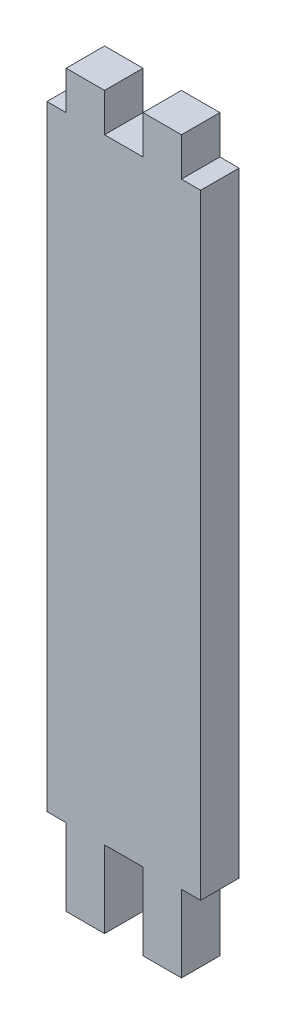
SolidWorks part; units mm, degrees
ref_plane "Front Plane" through (0, 0, 0) normal (0, 0, 1) x (1, 0, 0)
ref_plane "Top Plane" through (0, 0, 0) normal (0, 1, 0) x (1, 0, 0)
ref_plane "Right Plane" through (0, 0, 0) normal (1, 0, 0) x (0, 0, -1)
sketch "Sketch1" plane through (0, 0, 0) normal (0, 0, 1) x (1, 0, 0)
  line L0 (-7.5, 40) -> (-7.5, 45)
  line L1 (-10, -40) -> (-7.5, -40)
  line L2 (-10, -40) -> (-10, 40)
  line L3 (-10, 40) -> (-7.5, 40)
  line L4 (10, -40) -> (10, 40)
  line L5 (-10, -40) -> (10, 40) construction
  line L6 (-10, 40) -> (10, -40) construction
  line L7 (-7.5, 45) -> (-2.5, 45)
  line L8 (-2.5, 45) -> (-2.5, 40)
  line L9 (2.5, 40) -> (2.5, 45)
  line L10 (2.5, 45) -> (7.5, 45)
  line L11 (7.5, 45) -> (7.5, 40)
  line L12 (-2.5, 40) -> (2.5, 40)
  line L13 (7.5, 40) -> (10, 40)
  line L14 (-2.5, -40) -> (2.5, -40)
  line L16 (-7.5, -40) -> (-7.5, -45)
  line L20 (2.5, -40) -> (2.5, -45)
  line L23 (7.5, -40) -> (10, -40)
  line L24 (-7.5, -45) -> (-7.5, -50)
  line L25 (-7.5, -50) -> (-2.5, -50)
  line L26 (-2.5, -50) -> (-2.5, -40)
  line L27 (2.5, -45) -> (2.5, -50)
  line L28 (2.5, -50) -> (7.5, -50)
  line L29 (7.5, -50) -> (7.5, -40)
  point P0 (0, 0)
  point P19 (0, 0)
  point P24 (7.5, -45.7393)
  point P27 (-2.5, -45.954)
  dimension "D1" = 5
  dimension "D2" = 5
  dimension "D3" = 20
  dimension "D4" = 5
  dimension "D5" = 80
  dimension "D6" = 5
  dimension "D7" = 10
extrude "Boss-Extrude1" add sketch "Sketch1" along normal blind 5
